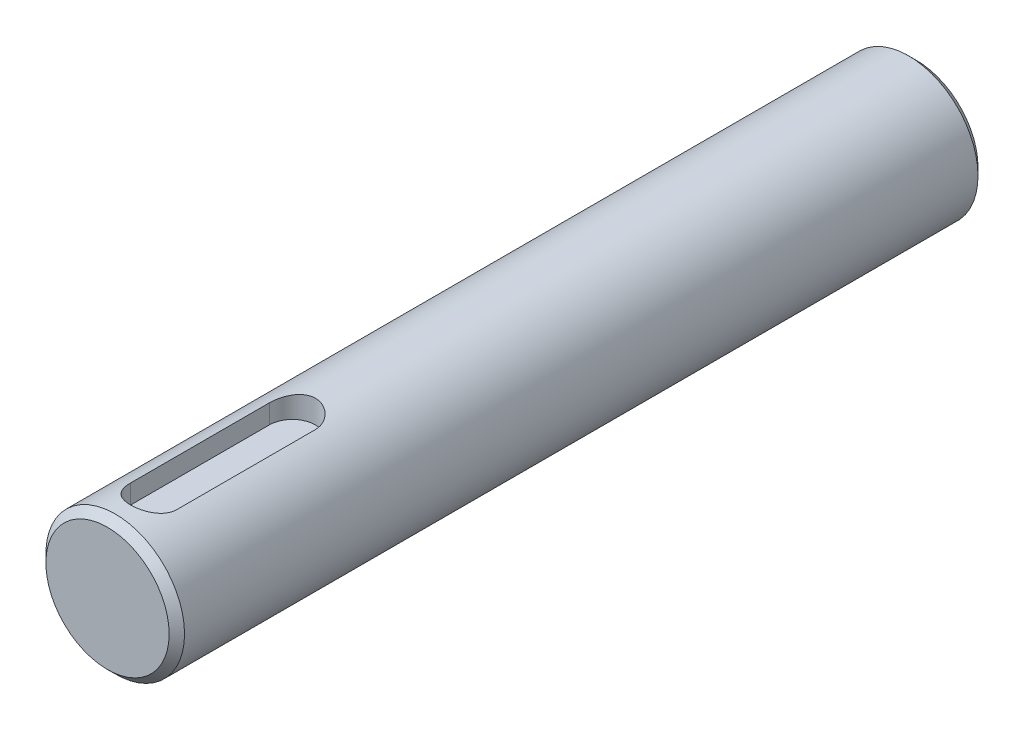
SolidWorks part; units mm, degrees
ref_plane "Ön Düzlem" through (0, 0, 0) normal (0, 0, 1) x (1, 0, 0)
ref_plane "Üst Düzlem" through (0, 0, 0) normal (0, 1, 0) x (1, 0, 0)
ref_plane "Sağ Düzlem" through (0, 0, 0) normal (1, 0, 0) x (0, 0, -1)
sketch "Çizim1" plane through (0, 0, 0) normal (0, 0, 1) x (1, 0, 0)
  circle A0 centre (0, 0) radius 9
  dimension "D1" = 18
extrude "Yükseklik-Ekstrüzyon1" add sketch "Çizim1" along normal blind 105
chamfer "Pah1" distance 1 angle 45 2 edges at (9, 0, 0) (9, 0, 105)
sketch "Çizim2" plane through (0, 0, 0) normal (0, 1, 0) x (1, 0, 0)
  line L0 (0, -105) -> (0, 0) construction
  line L1 (-8, -105) -> (8, -105) construction
  line L2 (0, -81) -> (0, -99) construction
  line L3 (3, -81) -> (3, -99)
  line L4 (-3, -81) -> (-3, -99)
  arc A0 (3, -81) -> (-3, -81) centre (0, -81) ccw
  arc A1 (-3, -99) -> (3, -99) centre (0, -99) ccw
  point P3 (0, -90)
  dimension "D2" = 3
  dimension "D1" = 18
  dimension "D3" = 6
extrude "Kes-Ekstrüzyon1" cut sketch "Çizim2" along normal through all from offset 6
